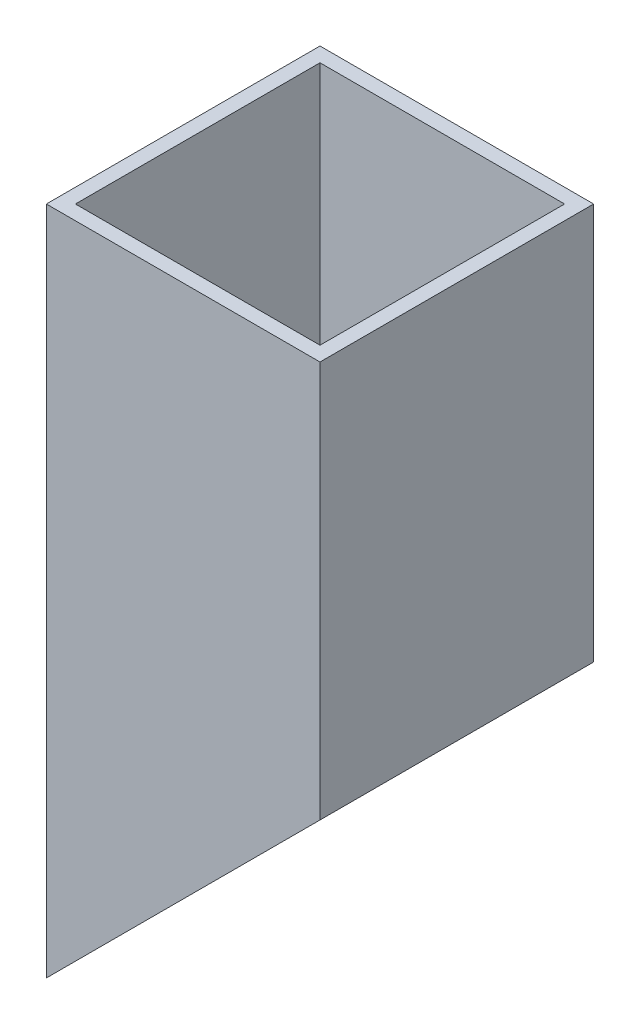
SolidWorks part; units mm, degrees
ref_plane "Alzado" through (0, 0, 0) normal (0, 0, 1) x (1, 0, 0)
ref_plane "Planta" through (0, 0, 0) normal (0, 1, 0) x (1, 0, 0)
ref_plane "Vista lateral" through (0, 0, 0) normal (1, 0, 0) x (0, 0, -1)
sketch "Croquis1" plane through (0, 0, 0) normal (0, 1, 0) x (1, 0, 0)
  line L1 (0, 0) -> (56.5, 0)
  line L2 (0, 0) -> (0, 56.5)
  line L3 (0, 56.5) -> (56.5, 56.5)
  line L4 (56.5, 0) -> (56.5, 56.5)
  dimension "D1" = 56.5
  dimension "D2" = 56.5
extrude "Saliente-Extruir1" add sketch "Croquis1" along normal blind 81.9
sketch "Croquis2" plane through (0, 0, 0) normal (0, 0, 1) x (1, 0, 0)
  line L0 (0, 0) -> (0, -56.5)
  line L1 (0, -56.5) -> (56.5, 0)
  line L2 (56.5, 0) -> (0, 0)
  dimension "D1" = 45
extrude "Saliente-Extruir2" add sketch "Croquis2" against normal up to surface (56.5 mm away) up to face at (28.25, 40.95, -56.5)
shell "Vaciado4" thickness 3
